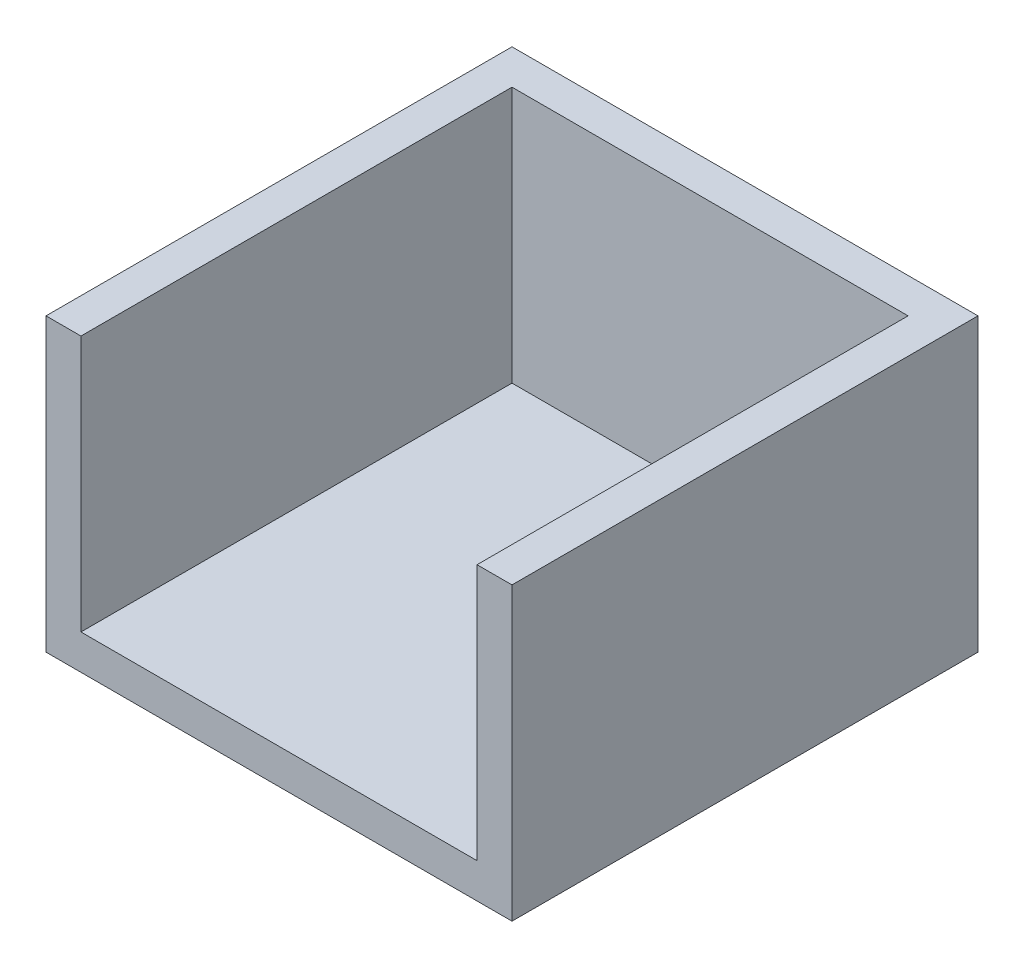
SolidWorks part; units mm, degrees
ref_plane "Front Plane" through (0, 0, 0) normal (0, 0, 1) x (1, 0, 0)
ref_plane "Top Plane" through (0, 0, 0) normal (0, 1, 0) x (1, 0, 0)
ref_plane "Right Plane" through (0, 0, 0) normal (1, 0, 0) x (0, 0, -1)
sketch "Sketch1" plane through (0, 0, 0) normal (0, 1, 0) x (1, 0, 0)
  line L1 (-20, 20) -> (20, 20)
  line L2 (-20, 20) -> (-20, -20)
  line L3 (-20, -20) -> (20, -20)
  line L4 (20, 20) -> (20, -20)
  line L5 (-20, 20) -> (20, -20) construction
  line L6 (-20, -20) -> (20, 20) construction
  point P0 (0, 0)
  dimension "D1" = 40
  dimension "D2" = 40
extrude "Boss-Extrude1" add sketch "Sketch1" along normal blind 25
sketch "Sketch2" plane through (0, 25, 0) normal (0, 1, 0) x (1, 0, 0)
  line L0 (0, 0) -> (0, -20)
  line L5 (-20, -20) -> (20, -20) construction
  line L6 (-17, -20) -> (17, -20)
  line L9 (17, -20) -> (-17, -20)
  line L10 (17, -20) -> (17, 17)
  line L11 (17, 17) -> (-17, 17)
  line L12 (-17, -20) -> (-17, 17)
  point P8 (0, -20)
extrude "Cut-Extrude1" cut sketch "Sketch2" against normal blind 22
